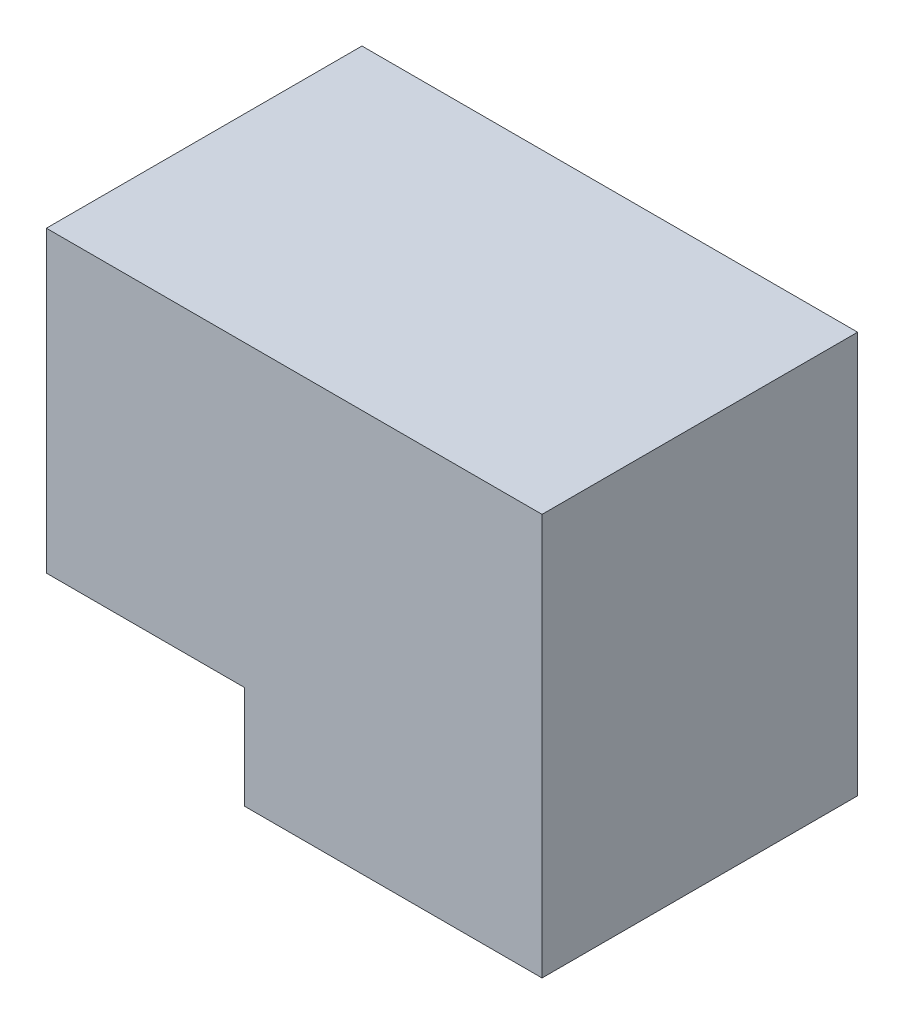
SolidWorks part; units mm, degrees
ref_plane "Front Plane" through (0, 0, 0) normal (0, 0, 1) x (1, 0, 0)
ref_plane "Top Plane" through (0, 0, 0) normal (0, 1, 0) x (1, 0, 0)
ref_plane "Right Plane" through (0, 0, 0) normal (1, 0, 0) x (0, 0, -1)
sketch "Sketch1" plane through (0, 0, 0) normal (0, 0, 1) x (1, 0, 0)
  line L5 (0, 0) -> (18.8119, 0)
  line L6 (18.8119, 0) -> (18.8119, -9.7712)
  line L7 (18.8119, -9.7712) -> (47.1212, -9.7712)
  line L8 (47.1212, -9.7712) -> (47.1212, 28.4005)
  line L9 (47.1212, 28.4005) -> (0, 28.4005)
  line L10 (0, 28.4005) -> (0, 0)
extrude "Boss-Extrude1" add sketch "Sketch1" along normal blind 30
sketch "Sketch2" plane through (0, 0, 0) normal (0, 0, 1) x (1, 0, 0)
  line L0 (0, 0) -> (18.8119, 0)
  line L7 (75.208, -37.5012) -> (117.2991, -41.1197)
  line L13 (18.8119, 0) -> (18.8119, -19.8806)
  line L14 (18.8119, -19.8806) -> (124.0251, -19.8806)
  line L23 (0, -32.1714) -> (0, 0)
  line L24 (124.0251, -19.8806) -> (124.0251, -32.1714)
  line L25 (124.0251, -32.1714) -> (0, -32.1714)
  line L26 (75.208, 29.4005) -> (75.208, -1.7593)
  line L27 (75.208, -1.7593) -> (148.7798, -1.7593)
  line L28 (148.7798, -1.7593) -> (148.7798, -81.0436)
  line L29 (148.7798, -81.0436) -> (188.8582, -81.0436)
  line L30 (188.8582, -81.0436) -> (188.8582, 54.4925)
  line L31 (188.8582, 54.4925) -> (-82.7555, 54.4925)
  line L32 (-82.7555, 54.4925) -> (-82.7555, 29.4005)
  line L33 (-82.7555, 29.4005) -> (75.208, 29.4005)
  line L35 (75.208, -57.3564) -> (117.2991, -53.7379)
  line L36 (47.1212, -9.7712) -> (47.1212, 28.4005) construction
  line L37 (-36.9366, 27.245) -> (-36.9366, -6.9732)
  line L38 (-36.9366, -6.9732) -> (-58.8476, -6.9732)
  line L39 (-58.8476, -6.9732) -> (-101.8478, -65.8765)
  line L40 (-101.8478, -65.8765) -> (102.5373, -227.7316)
  line L41 (102.5373, -227.7316) -> (75.208, -262.2421)
  line L42 (75.208, -262.2421) -> (-153.6033, -81.0436)
  line L43 (-153.6033, -81.0436) -> (-81.3971, 10.1359)
  line L44 (-81.3971, 10.1359) -> (-36.9366, 27.245)
  circle A1 centre (65.8601, -26.4588) radius 3.0821
  circle A2 centre (75.208, -47.4288) radius 9.9276
  circle A3 centre (117.2991, -47.4288) radius 6.3091
  circle A4 centre (75.208, -47.4288) radius 4.7507
  circle A5 centre (-124.6811, -81.0436) radius 9.9552
  spline S0 degree 3 poles (99.5438, -1.7593) (73.9392, -6.3738) (123.355, -5.5379) (78.5788, -10.0737) (115.0778, -14.0375) (73.4195, -15.1105) (115.0747, -18.4562) (95.7519, -19.8806) knots 0 0 0 0 0.279709 0.444337 0.604769 0.761111 1 1 1 1
  spline S1 degree 3 poles (75.208, 18.2067) (69.2351, -17.6099) (71.4952, 52.9141) (65.832, -10.6128) (61.5844, 42.1872) (57.4478, -11.7401) (55.2862, 39.7354) (50.1698, -18.1933) (51.3121, 39.3871) (47.1212, 13.8206) knots 0 0 0 0 0.215145 0.339789 0.462194 0.58876 0.706176 0.824134 1 1 1 1
